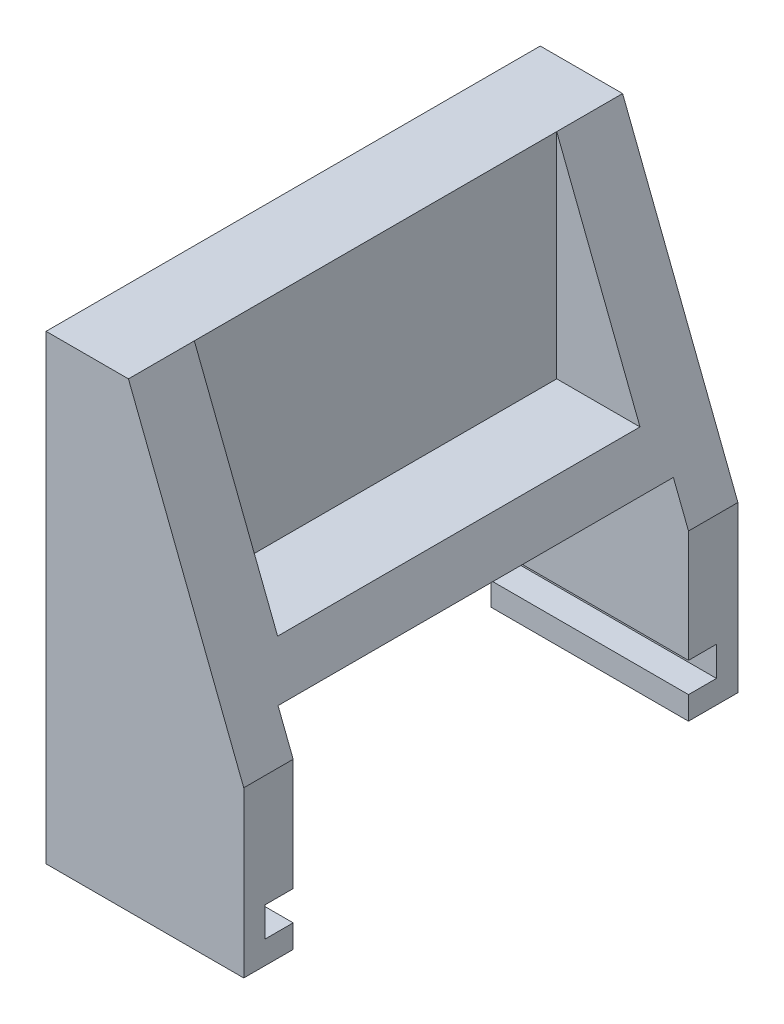
SolidWorks part; units mm, degrees
ref_plane "Front Plane" through (0, 0, 0) normal (0, 0, 1) x (1, 0, 0)
ref_plane "Top Plane" through (0, 0, 0) normal (0, 1, 0) x (1, 0, 0)
ref_plane "Right Plane" through (0, 0, 0) normal (1, 0, 0) x (0, 0, -1)
sketch "Sketch1" plane through (0, 0, 0) normal (0, 0, 1) x (1, 0, 0)
  line L0 (0, 0) -> (0, -28)
  line L1 (0, -28) -> (12, -28)
  line L2 (12, -28) -> (12, -18)
  line L3 (12, -18) -> (5, 0)
  line L4 (5, 0) -> (0, 0)
  dimension "D1" = 28
  dimension "D2" = 12
  dimension "D3" = 10
  dimension "D4" = 5
extrude "Boss-Extrude1" add sketch "Sketch1" against normal blind 30
sketch "Sketch4" plane through (0, 0, 0) normal (-1, 0, 0) x (0, 0, 1)
  line L0 (-30, 0) -> (-30, -28) construction
  line L1 (-27, -15.6386) -> (-3, -15.6386)
  line L2 (-27, -15.6386) -> (-27, -29.6386)
  line L3 (-27, -29.6386) -> (-3, -29.6386)
  line L4 (-3, -15.6386) -> (-3, -29.6386)
  point P4 (-27, -22.6386)
  dimension "D1" = 24
  dimension "D2" = 14
  dimension "D3" = 3
extrude "Cut-Extrude2" cut sketch "Sketch4" against normal blind 25 contours L2 L1 L4 L3
sketch "Sketch5" plane through (0, 0, 0) normal (-1, 0, 0) x (0, 0, 1)
  line L0 (-3, -15.6386) -> (-3, -28) construction
  line L1 (-3, -24.8) -> (-1.3, -24.8)
  line L2 (-3, -24.8) -> (-3, -26.6)
  line L3 (-3, -26.6) -> (-1.3, -26.6)
  line L4 (-1.3, -24.8) -> (-1.3, -26.6)
  line L5 (-3, -28) -> (0, -28) construction
  dimension "D1" = 1.8
  dimension "D2" = 1.7
  dimension "D3" = 1.4
extrude "Cut-Extrude3" cut sketch "Sketch5" against normal blind 15
ref_plane "Plane1" through (0, 0, -15) normal (0, 0, 1) x (1, 0, 0)
mirror "Mirror1" about plane through (0, 0, -15) normal (0, 0, 1) of "Cut-Extrude3"
sketch "Sketch6" plane through (0, 0, -15) normal (0, 0, 1) x (1, 0, 0)
  line L0 (5, 0) -> (5, -13)
  line L1 (5, -13) -> (10.0556, -13)
  line L2 (12, -18) -> (5, 0) construction
  line L3 (10.0556, -13) -> (5, 0)
  dimension "D1" = 13
extrude "Cut-Extrude4" cut sketch "Sketch6" against normal mid plane 22
ref_plane "Plane2" through (0, -15, 0) normal (0, 1, 0) x (1, 0, 0)
sketch "Sketch7" plane through (0, -15, 0) normal (0, 1, 0) x (1, 0, 0)
  line L0 (0, 15) -> (-3, 15)
  line L1 (0, 30) -> (0, 0) construction
  line L2 (-11.1958, 15) -> (11.1958, 15) construction
  line L3 (-3, 15) -> (-5.3561, 18.2325)
  line L4 (-5.3561, 18.2325) -> (-8.3561, 18.2325)
  line L5 (0, 12) -> (-4.5257, 12)
  line L6 (-4.5257, 12) -> (-6.8818, 15.2325)
  line L7 (-6.8818, 15.2325) -> (-8.3561, 15.2325)
  line L8 (-8.3561, 18.2325) -> (-8.3561, 15.2325)
  line L9 (0, 12) -> (0, 15)
  dimension "D1" = 3
  dimension "D2" = 3
  dimension "D3" = 4
  dimension "D4" = 3
extrude "Boss-Extrude2" add sketch "Sketch7" along normal blind 3
sketch "Sketch8" plane through (0, -15, 0) normal (0, -1, 0) x (-1, 0, 0)
  line L0 (8.3561, 18.2325) -> (8.3561, 15.2325) construction
  line L3 (5.3561, 18.2325) -> (8.3561, 18.2325) construction
  circle A0 centre (6.8561, 16.6325) radius 1.25
  point P6 (6.3554, 18.2325)
  point P7 (6.3165, 18.2325)
  dimension "D1" = 2.5
  dimension "D2" = 1.5
  dimension "D3" = 1.6
extrude "Boss-Extrude3" add sketch "Sketch8" along normal blind 4
fillet "Fillet3" radius 1 1 edges at (-6.8561, -19, -17.8825)
